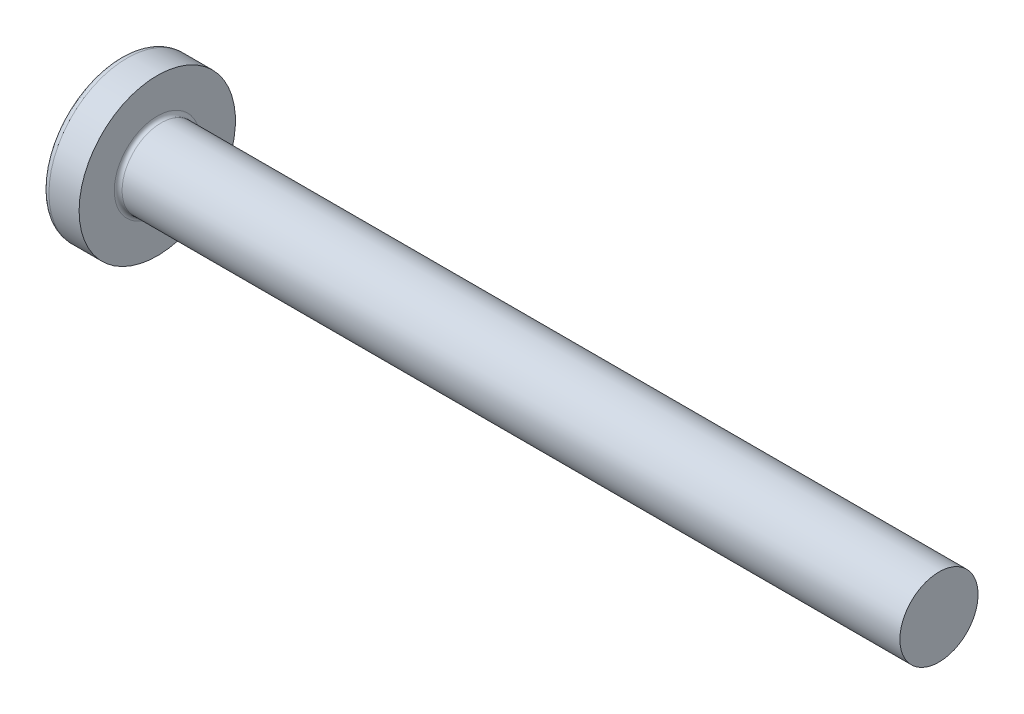
SolidWorks part; units mm, degrees
material "AISI 304"
ref_plane "Plane1" through (0, 0, 0) normal (0, 0, 1) x (1, 0, 0)
ref_plane "Plane2" through (0, 0, 0) normal (0, 1, 0) x (1, 0, 0)
ref_plane "Plane3" through (0, 0, 0) normal (1, 0, 0) x (0, 0, -1)
sketch "BodySke" plane through (0, 0, 0) normal (0, 0, 1) x (1, 0, 0)
  line L0 (3.1, 2) -> (3.1, 4)
  line L1 (3.45, 6.35) -> (3.45, -3.175) construction
  line L2 (-25.4, 0) -> (127, 0) construction
  line L3 (43.1, 0) -> (0, 0)
  line L4 (3.1, 2) -> (43.1, 2)
  line L5 (43.1, 2) -> (43.1, 0)
  line L6 (1.5553, 4) -> (3.1, 4)
  line L8 (37.1, 6.35) -> (37.1, -3.175) construction
  arc A0 (1.2654, 3.8534) -> (0, 0) centre (6.5, 0) ccw
  arc A2 (1.2654, 3.8534) -> (1.5553, 4) centre (1.5553, 3.64) cw
  dimension "Head_crown_rad" = 6.5
  dimension "Head_fillet_rad" = 0.36
  dimension "4" = 40
  dimension "Head_ht" = 3.1
  dimension "Head_dia" = 8
  dimension "Advance" = 0.7
  dimension "Thread_nom" = 6
  dimension "Diameter" = 4
revolve "Base-Revolve" add sketch "BodySke"
cosmetic thread "ThreadCosmetic" [suppressed]
fillet "Fillet1" radius 0.2 1 edges at (3.1, 0, 2)
sketch "Sketch3" plane through (0, 0, 0) normal (1, 0, 0) x (0, 0, -1)
  line L0 (0.515, -2.15) -> (-0.515, -2.15)
  line L1 (0.515, -2.15) -> (0.515, 2.15)
  line L2 (-0.515, 2.15) -> (0.515, 2.15)
  line L3 (-0.515, 2.15) -> (-0.515, -2.15)
  dimension "Cross_dia" = 4.3
  dimension "D1" = 2.15
  dimension "Cross_width" = 1.03
  dimension "D2" = 0.515
ref_plane "Plane4" through (2.34, 0, 0) normal (1, 0, 0) x (0, 0, -1)
sketch "Sketch4" plane through (2.34, 0, 0) normal (1, 0, 0) x (0, 0, -1)
  line L0 (0.515, -0.9833) -> (-0.515, -0.9833)
  line L1 (0.515, -0.9833) -> (0.515, 0.9833)
  line L2 (-0.515, 0.9833) -> (0.515, 0.9833)
  line L3 (-0.515, 0.9833) -> (-0.515, -0.9833)
  dimension "D1" = 1.03
  dimension "D2" = 1.9666
  dimension "D3" = 0.515
  dimension "D4" = 0.9833
loft "Recess" cut profiles "Sketch3", "Sketch4"
pattern_circular "RecPat" count 2 every 90 about axis through (0, 0, 0) along (1, 0, 0) of "Recess"
sketch "RecCorSke" plane through (0, 0, 0) normal (0, 0, 1) x (1, 0, 0)
  line L0 (-3.175, 0) -> (15.875, 0) construction
  line L1 (-25.4, 0) -> (127, 0) construction
  line L2 (0, 0) -> (0, 1.0146)
  line L3 (0, 1.0146) -> (2.34, 0.851)
  line L4 (2.34, 0.851) -> (2.6165, 0)
  line L5 (2.6165, 0) -> (0, 0)
  dimension "Diameter" = 1.702
  dimension "Depth" = 2.34
  dimension "Draft_angle" = 4
  dimension "Bottom_angle" = 18
revolve "RecessCore" cut sketch "RecCorSke" angle 360 about L0
sketch "ThdSchSke" plane through (0, 0, 0) normal (0, 0, 1) x (1, 0, 0)
  line L0 (42.1, -1.61) -> (41.8269, -2)
  line L1 (42.1, -1.61) -> (42.3731, -2)
  line L2 (42.3731, -2) -> (42.3731, -2.5)
  line L3 (-3.175, 0) -> (5.1513, 0) construction
  line L5 (42.3731, -2.5) -> (41.8269, -2.5)
  line L6 (41.8269, -2.5) -> (41.8269, -2)
  dimension "Diameter" = 4
  dimension "SideAngle" = 55
  dimension "VeeAngle" = 70
  dimension "Thread_minor" = 3.22
  dimension "Overcut" = 5
  dimension "Start" = 42.1
revolve "ThreadSchematic" [suppressed] cut sketch "ThdSchSke" angle 360 about L3
pattern_linear "ThdSchPat" [suppressed]
sketch "草图1" plane through (43.1, 0, 0) normal (1, 0, 0) x (0, 0, -1)
  circle A0 centre (0, 0) radius 2 construction
  circle A1 centre (0, 0) radius 2
equation "\"D1@Sketch3\" = \"Cross_dia@Sketch3\" / 2"
equation "\"D2@Sketch3\" = \"Cross_width@Sketch3\" / 2"
equation "\"Depth@RecCorSke\" = \"Cross_depth@Plane4\""
equation "\"D1@Sketch4\" = \"Cross_width@Sketch3\""
equation "\"D2@Sketch4\" = \"Cross_dia@Sketch3\" - 2.0 * \"Cross_depth@Plane4\" * tan(26.5  * 0.017453292)"
equation "\"D3@Sketch4\" = \"D1@Sketch4\" / 2"
equation "\"D4@Sketch4\" = \"D2@Sketch4\" / 2"
equation "\"Thread_length@ThreadCosmetic\" = ((sgn( (\"4@BodySke\" - \"Advance@BodySke\" * 2.0 ) - \"Thread_nom@BodySke\" )-1)*( (\"4@BodySke\" - \"Advance@BodySke\" * 2.0 ) - \"Thread_nom@BodySke\" ))/-2+ \"Thread_nom@BodySke\""
equation "\"Thread_minor@ThdSchSke\" = \"Thread_minor@ThreadCosmetic\""
equation "\"Diameter@ThdSchSke\" = \"Diameter@BodySke\""
equation "\"Overcut@ThdSchSke\" = \"Diameter@BodySke\" * 1.25"
equation "\"Start@ThdSchSke\" = \"Head_ht@BodySke\" + \"4@BodySke\" - \"Thread_length@ThreadCosmetic\"  '---Non-countersunk---"
equation "\"Num_threads@ThdSchPat\" = int( \"Thread_length@ThreadCosmetic\" / \"Advance@BodySke\" + 0.999 )  + 1"
equation "\"Advance@ThdSchPat\" = \"Thread_length@ThreadCosmetic\" /  (\"Num_threads@ThdSchPat\" - 1) 'relax it"
